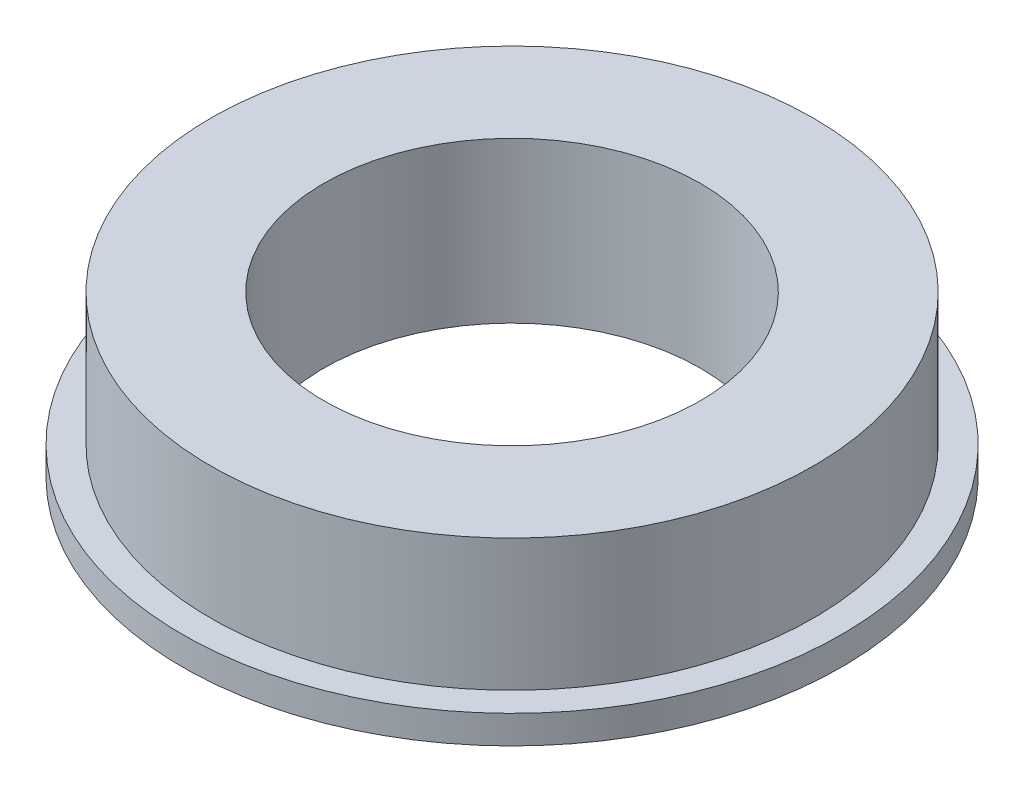
SolidWorks part; units mm, degrees
ref_plane "前视基准面" through (0, 0, 0) normal (0, 0, 1) x (1, 0, 0)
ref_plane "上视基准面" through (0, 0, 0) normal (0, 1, 0) x (1, 0, 0)
ref_plane "右视基准面" through (0, 0, 0) normal (1, 0, 0) x (0, 0, -1)
sketch "草图1" plane through (0, 0, 0) normal (0, 0, 1) x (1, 0, 0)
  line L0 (16, 1.5) -> (16, 8.5)
  line L1 (16, 8.5) -> (10, 8.5)
  line L2 (10, 8.5) -> (10, 0)
  line L3 (10, 0) -> (17.5, 0)
  line L4 (17.5, 0) -> (17.5, 1.5)
  line L5 (17.5, 1.5) -> (16, 1.5)
  line L6 (0, 7) -> (0, 0) construction
  dimension "D1" = 1.5
  dimension "D2" = 6
  dimension "D3" = 7
revolve "旋转1" add sketch "草图1" angle 360 about L6
